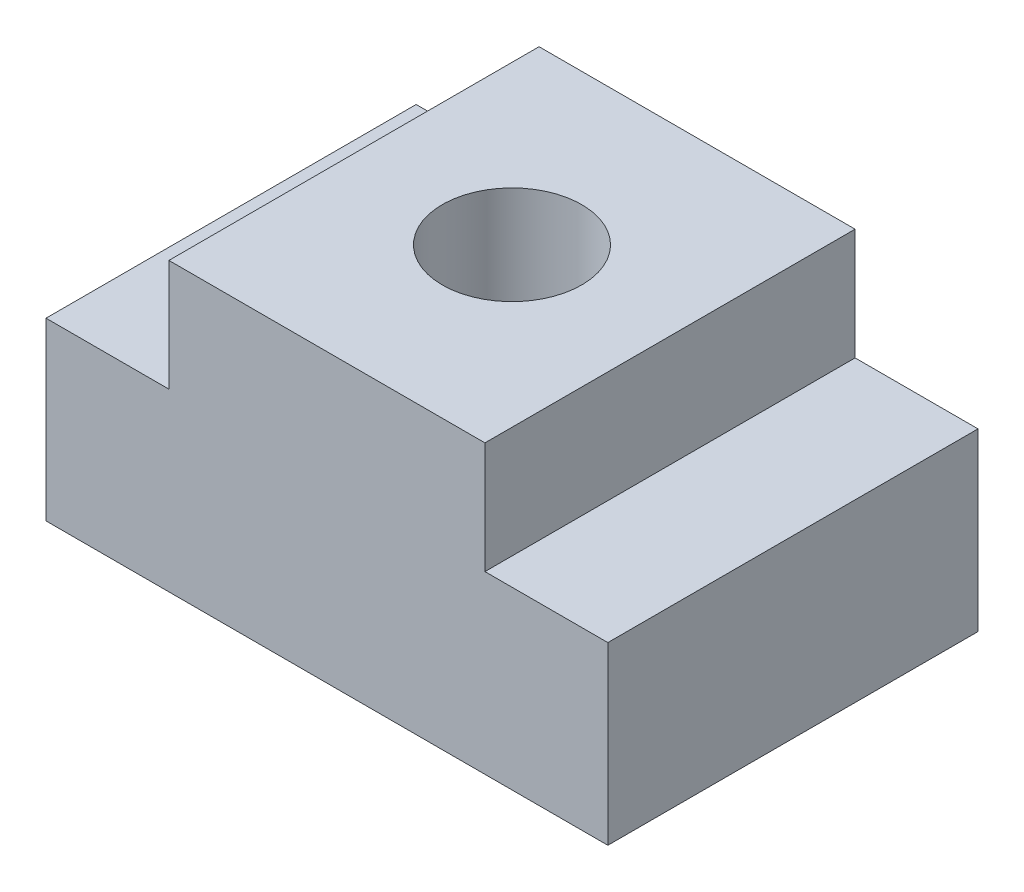
SolidWorks part; units mm, degrees
ref_plane "Front Plane" through (0, 0, 0) normal (0, 0, 1) x (1, 0, 0)
ref_plane "Top Plane" through (0, 0, 0) normal (0, 1, 0) x (1, 0, 0)
ref_plane "Right Plane" through (0, 0, 0) normal (1, 0, 0) x (0, 0, -1)
sketch "Sketch1" plane through (0, 0, 0) normal (0, 0, 1) x (1, 0, 0)
  line L0 (-16, 0) -> (16, 0)
  line L1 (-16, 0) -> (-16, 10)
  line L2 (-16, 10) -> (-9, 10)
  line L3 (-9, 10) -> (-9, 16.35)
  line L4 (-9, 16.35) -> (9, 16.35)
  line L5 (0, 16.35) -> (0, 0) construction
  line L6 (9, 10) -> (9, 16.35)
  line L7 (16, 10) -> (9, 10)
  line L8 (16, 0) -> (16, 10)
  point P1 (0, 0)
  point P4 (0, 0)
  dimension "D1" = 16
  dimension "D2" = 10
  dimension "D3" = 7
  dimension "D4" = 6.35
extrude "Boss-Extrude1" add sketch "Sketch1" along normal blind 21.082
hole_wizard "3/8-16 Tapped Hole1" positions "Sketch2" profile "Sketch3" tap size "3/8-16" standard "ANSI Inch" end condition through all
sketch "Sketch2" plane through (0, 16.35, 0) normal (0, 1, 0) x (1, 0, 0)
  line L0 (-9, -21.082) -> (-9, 0) construction
  point P0 (0, -10.541)
  point P7 (-9, -10.541)
sketch "Sketch3" plane through (0, 16.35, 10.541) normal (1, 0, 0) x (0, 0, 1)
  line L0 (0, 0) -> (0, 16.35)
  line L1 (0, 16.35) -> (3.9687, 16.35)
  line L2 (3.9687, 16.35) -> (3.9687, 0)
  line L5 (3.9687, 0) -> (0, 0)
  line L11 (0, -6.35) -> (0, 107.95) construction
  dimension "Thru Tap Drill Dia." = 7.9375
  dimension "Thru Tap Drill Depth" = 16.35
cosmetic thread "Hole Thread1" parameters "D2"=9.525
